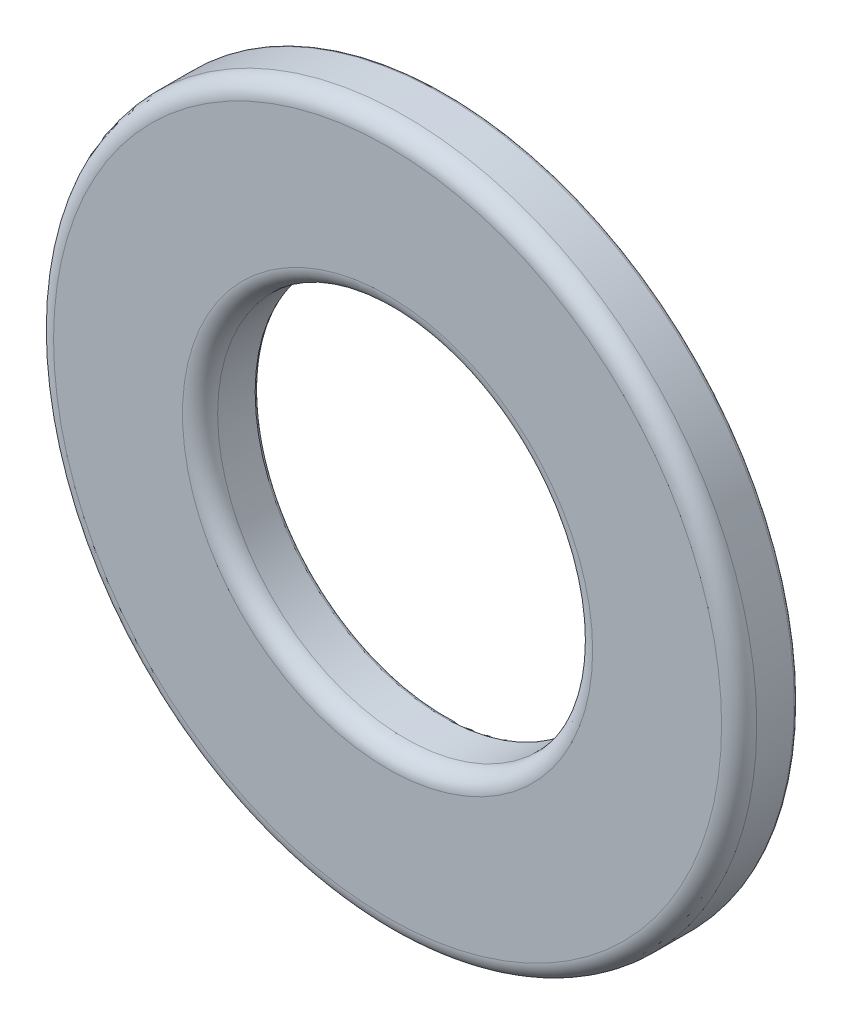
SolidWorks part; units mm, degrees
material "AISI 316 Stainless Steel Sheet (SS)"
ref_plane "Front Plane" through (0, 0, 0) normal (0, 0, 1) x (1, 0, 0)
ref_plane "Top Plane" through (0, 0, 0) normal (0, 1, 0) x (1, 0, 0)
ref_plane "Right Plane" through (0, 0, 0) normal (1, 0, 0) x (0, 0, -1)
sketch "Sketch1" plane through (0, 0, 0) normal (0, 0, 1) x (1, 0, 0)
  circle A0 centre (0, 0) radius 3 construction
  circle A1 centre (0, 0) radius 1.6 construction
  point P6 (0, 3)
  dimension "OD" = 6
  dimension "ID" = 3.2
sketch "Sketch2" plane through (0, 0, 0) normal (1, 0, 0) x (0, 0, -1)
  line L1 (-0.25, 3) -> (0.25, 3) construction
  point P0 (-0.25, 3)
  point P3 (0.25, 3)
  point P11 (-0.25, 3)
  point P13 (0.25, 3)
  dimension "Thickness" = 0.5
sketch "Sketch3" plane through (0, 0, 0) normal (0, 0, 1) x (1, 0, 0)
  circle A0 centre (0, 0) radius 1.6 construction
  circle A1 centre (0, 0) radius 3 construction
  circle A2 centre (0, 0) radius 1.6
  circle A3 centre (0, 0) radius 3
extrude "Boss-Extrude1" add sketch "Sketch3" against normal up to vertex (0.25 mm away) and the other way up to vertex (0.25 mm away) up to point (0, 3, -0.25) other way up to point (0, 3, 0.25)
fillet "Fillet1" radius 0.15 2 edges at (1.6, 0, 0.25) (3, 0, 0.25)
fillet "Fillet3" radius 0.03 2 edges at (3, 0, -0.25) (1.6, 0, -0.25)
equation "\"D1@Fillet1\"=\"OD@Sketch1\"*.025"
equation "\"D1@Fillet2\"=\"OD@Sketch1\"*.02"
equation "\"D1@Fillet3\"=\"OD@Sketch1\"*.005"
